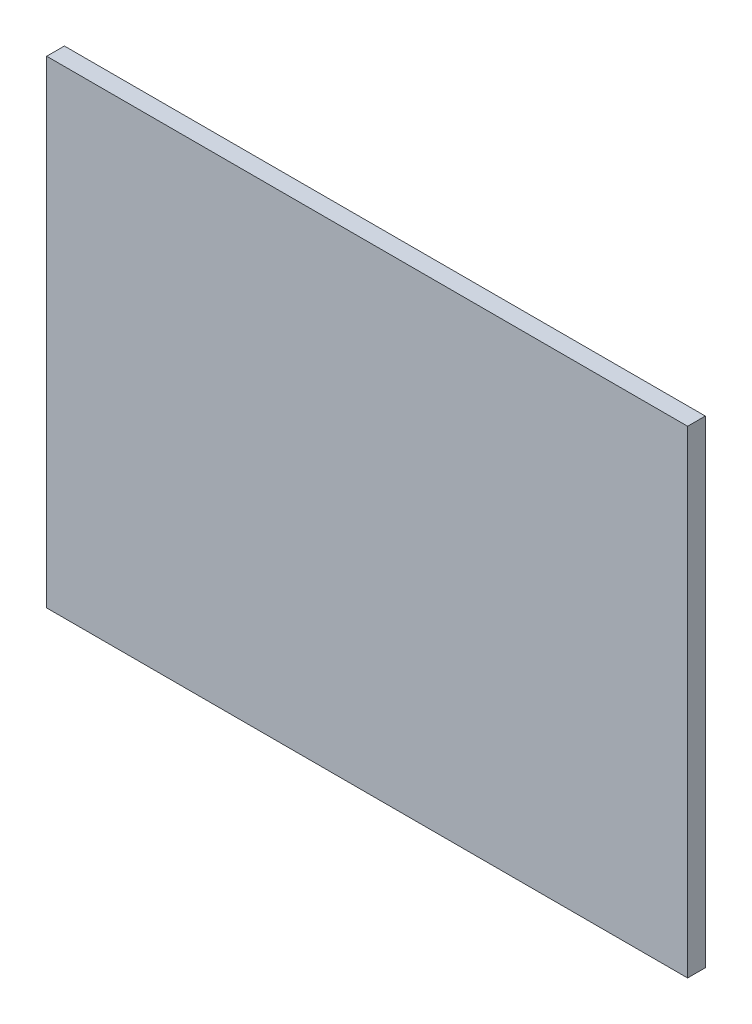
SolidWorks part; units mm, degrees
ref_plane "Front Plane" through (0, 0, 0) normal (0, 0, 1) x (1, 0, 0)
ref_plane "Top Plane" through (0, 0, 0) normal (0, 1, 0) x (1, 0, 0)
ref_plane "Right Plane" through (0, 0, 0) normal (1, 0, 0) x (0, 0, -1)
sketch "Sketch1" plane through (0, 0, 0) normal (0, 0, 1) x (1, 0, 0)
  line L0 (90.6195, -3.175) -> (90.6195, 3.175) construction
  line L1 (90.6195, -15.875) -> (-139.3499, -15.875)
  line L2 (90.6195, -15.875) -> (90.6195, 155.575)
  line L3 (90.6195, 155.575) -> (-139.3499, 155.575)
  line L4 (-139.3499, -15.875) -> (-139.3499, 155.575)
  line L5 (113.7824, 69.85) -> (-193.0608, 69.85) construction
  line L6 (90.6195, -3.175) -> (-26.6981, -3.175) construction
  line L7 (90.6195, 142.875) -> (-122.1584, 142.875) construction
  ellipse E0 centre (47.625, 171.7384) end of major axis (47.625, -44.1616) minor radius 186.9749 (190.7889, 310.6087) -> (190.7889, 32.8681) ccw construction
  dimension "D1" = 12.7
extrude "Boss-Extrude1" add sketch "Sketch1" along normal blind 6.35
